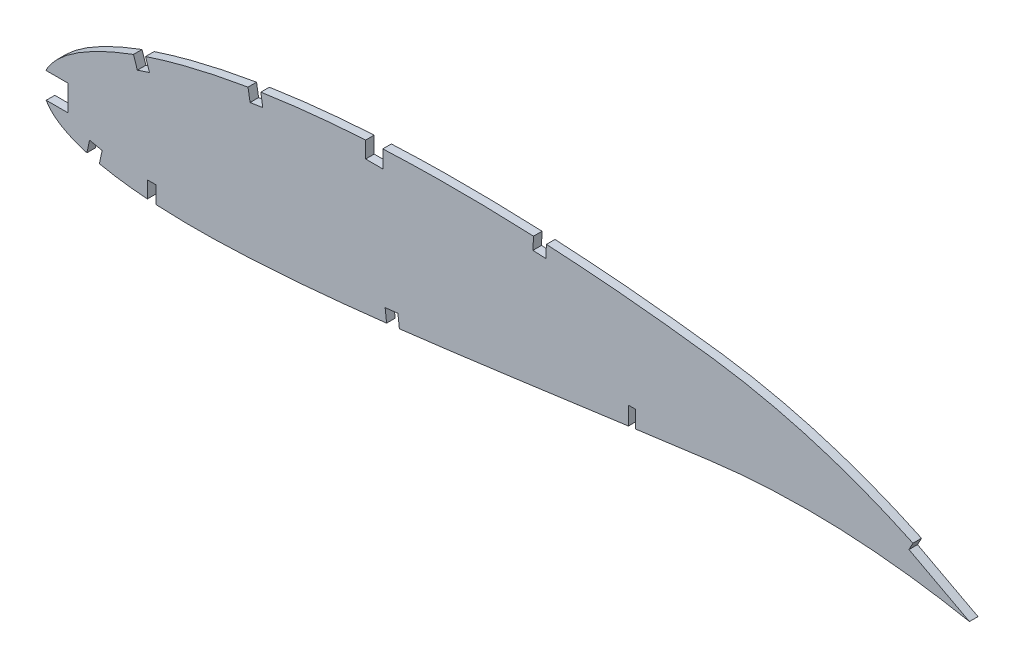
SolidWorks part; units mm, degrees
ref_plane "Front Plane" through (0, 0, 0) normal (0, 0, 1) x (1, 0, 0)
ref_plane "Top Plane" through (0, 0, 0) normal (0, 1, 0) x (1, 0, 0)
ref_plane "Right Plane" through (0, 0, 0) normal (1, 0, 0) x (0, 0, -1)
curve "Curve4"
  spline degree 3 poles (349.8746, 0.5455, 0) (349.8478, 0.562, 0) (349.7407, 0.6282, 0) (349.4993, 0.7762, 0) (349.0975, 1.0228, 0) (348.5349, 1.3661, 0) (347.8121, 1.8054, 0) (346.9286, 2.3375, 0) (345.885, 2.9606, 0) (344.6816, 3.6719, 0) (343.3185, 4.4681, 0) (341.7962, 5.3458, 0) (340.1148, 6.3001, 0) (338.275, 7.3272, 0) (336.2775, 8.422, 0) (334.1225, 9.5798, 0) (331.8109, 10.7946, 0) (329.3436, 12.0612, 0) (326.721, 13.3725, 0) (323.9443, 14.7232, 0) (321.0145, 16.1064, 0) (317.9326, 17.5149, 0) (314.7004, 18.9428, 0) (311.3186, 20.3813, 0) (307.7893, 21.8242, 0) (304.114, 23.2633, 0) (300.2949, 24.6919, 0) (296.3333, 26.1008, 0) (292.2323, 27.484, 0) (287.9939, 28.8323, 0) (283.6211, 30.1385, 0) (279.1164, 31.3942, 0) (274.4837, 32.5927, 0) (269.7257, 33.7256, 0) (264.8466, 34.785, 0) (259.8503, 35.7648, 0) (254.7409, 36.655, 0) (249.5326, 37.455, 0) (244.3091, 38.1205, 0) (239.0964, 38.7732, 0) (233.8915, 39.3864, 0) (228.623, 39.9736, 0) (223.2959, 40.5315, 0) (217.9156, 41.0583, 0) (212.4874, 41.5519, 0) (207.0171, 42.0107, 0) (201.5099, 42.4322, 0) (195.9716, 42.8157, 0) (190.4077, 43.1578, 0) (184.8241, 43.4583, 0) (179.2266, 43.7151, 0) (173.6208, 43.9264, 0) (168.0128, 44.0909, 0) (162.4085, 44.2071, 0) (156.8137, 44.2742, 0) (151.2345, 44.2904, 0) (145.6768, 44.2555, 0) (140.1465, 44.1681, 0) (134.6496, 44.0271, 0) (129.192, 43.8323, 0) (123.7796, 43.5837, 0) (118.4182, 43.2792, 0) (113.1138, 42.9209, 0) (107.8721, 42.5071, 0) (102.6991, 42.0378, 0) (97.6, 41.5149, 0) (92.5806, 40.937, 0) (87.6463, 40.3058, 0) (82.8024, 39.6225, 0) (78.0545, 38.8867, 0) (73.4074, 38.1005, 0) (68.8664, 37.2648, 0) (64.4362, 36.3819, 0) (60.1215, 35.4522, 0) (55.9271, 34.4784, 0) (51.8572, 33.4622, 0) (47.9162, 32.4055, 0) (44.1081, 31.3108, 0) (40.4368, 30.1806, 0) (36.9066, 29.0161, 0) (33.52, 27.8218, 0) (30.2813, 26.5985, 0) (27.193, 25.3499, 0) (24.2586, 24.0778, 0) (21.4804, 22.7861, 0) (18.8615, 21.4761, 0) (16.4038, 20.1517, 0) (14.1097, 18.8148, 0) (11.9815, 17.4679, 0) (10.02, 16.1143, 0) (8.2279, 14.7551, 0) (6.606, 13.3936, 0) (5.1551, 12.0318, 0) (3.8773, 10.6708, 0) (2.7727, 9.3129, 0) (1.8427, 7.9591, 0) (1.0874, 6.6108, 0) (0.5085, 5.269, 0) (0.1055, 3.9344, 0) (-0.1151, 2.6089, 0) (-0.17, 1.2916, 0) (-0.0566, 0.4299, 0) (0, 0, 0) knots 0 0 0 0 0.000254 0.001015 0.002283 0.004057 0.006331 0.009105 0.012374 0.016134 0.02038 0.025106 0.030306 0.035972 0.0421 0.048678 0.055702 0.06316 0.071046 0.07935 0.088063 0.097176 0.106678 0.116562 0.126814 0.137428 0.148394 0.1597 0.171338 0.183298 0.19557 0.208144 0.221012 0.234162 0.247587 0.261277 0.275223 0.289414 0.303771 0.317689 0.331784 0.34604 0.360444 0.374983 0.38964 0.404403 0.419257 0.434187 0.449177 0.464215 0.479284 0.49437 0.509458 0.524532 0.539579 0.554583 0.56953 0.584403 0.599191 0.613877 0.628447 0.642889 0.657186 0.671326 0.685294 0.699078 0.712665 0.726043 0.739198 0.752118 0.764792 0.777208 0.789356 0.801224 0.812804 0.824083 0.835055 0.84571 0.856038 0.866034 0.875689 0.884998 0.893953 0.902553 0.910789 0.918661 0.926166 0.933303 0.940071 0.946475 0.952518 0.958205 0.963547 0.968557 0.97325 0.977651 0.981787 0.985694 0.989415 0.993001 0.996508 1 1 1 1
curve "Curve5"
  spline degree 3 poles (0, 0, 0) (0.0898, -0.4241, 0) (0.27, -1.2744, 0) (0.7593, -2.4983, 0) (1.4064, -3.6749, 0) (2.2249, -4.801, 0) (3.2093, -5.8763, 0) (4.3574, -6.9018, 0) (5.6682, -7.8772, 0) (7.1398, -8.8018, 0) (8.7703, -9.6767, 0) (10.5577, -10.5014, 0) (12.5004, -11.2756, 0) (14.5962, -11.9982, 0) (16.8428, -12.6703, 0) (19.2378, -13.2904, 0) (21.7785, -13.8593, 0) (24.4626, -14.3755, 0) (27.2871, -14.8396, 0) (30.2491, -15.2513, 0) (33.3455, -15.6108, 0) (36.5732, -15.9174, 0) (39.9292, -16.1718, 0) (43.41, -16.3741, 0) (47.0123, -16.5249, 0) (50.7326, -16.6238, 0) (54.5673, -16.6722, 0) (58.5129, -16.6709, 0) (62.5656, -16.6195, 0) (66.7219, -16.5208, 0) (70.9777, -16.3742, 0) (75.3293, -16.1816, 0) (79.7728, -15.9448, 0) (84.3041, -15.6646, 0) (88.9192, -15.3423, 0) (93.6142, -14.9805, 0) (98.3848, -14.58, 0) (103.2269, -14.1432, 0) (108.136, -13.6724, 0) (113.1081, -13.1689, 0) (118.1387, -12.6351, 0) (123.2233, -12.0729, 0) (128.3576, -11.4851, 0) (133.537, -10.8728, 0) (138.7569, -10.2396, 0) (144.0126, -9.5866, 0) (149.2997, -8.9164, 0) (154.6133, -8.2321, 0) (159.9485, -7.5337, 0) (165.3008, -6.826, 0) (170.6651, -6.1086, 0) (176.0366, -5.3852, 0) (181.4105, -4.6578, 0) (186.7814, -3.9269, 0) (192.1447, -3.1954, 0) (197.4954, -2.4653, 0) (202.8282, -1.7368, 0) (208.1384, -1.0133, 0) (213.4205, -0.2949, 0) (218.6696, 0.417, 0) (223.8809, 1.1204, 0) (229.0493, 1.8142, 0) (234.1695, 2.4981, 0) (239.2364, 3.1723, 0) (244.169, 3.8163, 0) (248.9545, 4.4645, 0) (253.6088, 4.9959, 0) (258.2053, 5.4495, 0) (262.7485, 5.8213, 0) (267.2331, 6.1168, 0) (271.654, 6.3381, 0) (276.0058, 6.4882, 0) (280.283, 6.5716, 0) (284.4804, 6.5904, 0) (288.5922, 6.5507, 0) (292.613, 6.4555, 0) (296.5372, 6.3093, 0) (300.3594, 6.1169, 0) (304.0742, 5.8836, 0) (307.6759, 5.6128, 0) (311.1595, 5.3108, 0) (314.5196, 4.9821, 0) (317.7512, 4.6304, 0) (320.8494, 4.263, 0) (323.8094, 3.8825, 0) (326.6267, 3.4951, 0) (329.2966, 3.1046, 0) (331.8151, 2.7161, 0) (334.1781, 2.3332, 0) (336.3819, 1.9612, 0) (338.423, 1.6033, 0) (340.2977, 1.2632, 0) (342.0037, 0.9451, 0) (343.5374, 0.6506, 0) (344.8968, 0.3845, 0) (346.0794, 0.1481, 0) (347.0834, -0.0554, 0) (347.9072, -0.2251, 0) (348.5494, -0.3583, 0) (349.0088, -0.4551, 0) (349.2849, -0.5128, 0) (349.4076, -0.5389, 0) (349.4382, -0.5455, 0) knots 0 0 0 0 0.003638 0.007293 0.011028 0.014901 0.018963 0.023258 0.027821 0.032679 0.037853 0.043362 0.049215 0.055422 0.061989 0.068918 0.076211 0.083868 0.091887 0.100266 0.109 0.118085 0.127515 0.137285 0.147388 0.157816 0.168563 0.179619 0.190977 0.202627 0.21456 0.226767 0.239236 0.251959 0.264924 0.27812 0.291536 0.30516 0.318981 0.332985 0.347163 0.361499 0.375981 0.390597 0.405333 0.420175 0.43511 0.450124 0.465203 0.480333 0.495501 0.51069 0.525887 0.541078 0.556247 0.571382 0.586466 0.601485 0.616424 0.631269 0.646007 0.660621 0.675098 0.689423 0.703582 0.716908 0.730009 0.742952 0.755726 0.76832 0.780724 0.792927 0.804916 0.816679 0.828204 0.839475 0.850481 0.861208 0.871639 0.881763 0.891564 0.901027 0.910139 0.918884 0.927249 0.935221 0.942785 0.949928 0.956638 0.962904 0.968712 0.974054 0.978918 0.983297 0.98718 0.990561 0.993433 0.995791 0.99763 0.998946 0.999737 1 1 1 1
sketch "Sketch1" plane through (0, 0, 0) normal (0, 0, 1) x (1, 0, 0)
  line L24 (349.8746, 0.5455) -> (352.7074, -1.2046)
  line L25 (349.4382, -0.5455) -> (352.7074, -1.2046)
  spline S1 degree 3 poles (-4826.1735, -1302.2326) (84.7421, 69.7383) (-8.0065, 19.4278) (0.7593, -2.4983) (1.4064, -3.6749) (2.2249, -4.801) (3.2093, -5.8763) (4.3574, -6.9018) (5.6682, -7.8772) (7.1398, -8.8018) (8.7703, -9.6767) (10.5577, -10.5014) (12.5004, -11.2756) (14.5962, -11.9982) (16.8428, -12.6703) (19.2378, -13.2904) (21.7785, -13.8593) (24.4626, -14.3755) (27.2871, -14.8396) (30.2491, -15.2513) (33.3455, -15.6108) (36.5732, -15.9174) (39.9292, -16.1718) (43.41, -16.3741) (47.0123, -16.5249) (50.7326, -16.6238) (54.5673, -16.6722) (58.5129, -16.6709) (62.5656, -16.6195) (66.7219, -16.5208) (70.9777, -16.3742) (75.3293, -16.1816) (79.7728, -15.9448) (84.3041, -15.6646) (88.9192, -15.3423) (93.6142, -14.9805) (98.3848, -14.58) (103.2269, -14.1432) (108.136, -13.6724) (113.1081, -13.1689) (118.1387, -12.6351) (123.2233, -12.0729) (128.3576, -11.4851) (133.537, -10.8728) (138.7569, -10.2396) (144.0126, -9.5866) (149.2997, -8.9164) (154.6133, -8.2321) (159.9485, -7.5337) (165.3008, -6.826) (170.6651, -6.1086) (176.0366, -5.3852) (181.4105, -4.6578) (186.7814, -3.9269) (192.1447, -3.1954) (197.4954, -2.4653) (202.8282, -1.7368) (208.1384, -1.0133) (213.4205, -0.2949) (218.6696, 0.417) (223.8809, 1.1204) (229.0493, 1.8142) (234.1695, 2.4981) (239.2364, 3.1723) (244.169, 3.8163) (248.9545, 4.4645) (253.6088, 4.9959) (258.2053, 5.4495) (262.7485, 5.8213) (267.2331, 6.1168) (271.654, 6.3381) (276.0058, 6.4882) (280.283, 6.5716) (284.4804, 6.5904) (288.5922, 6.5507) (292.613, 6.4555) (296.5372, 6.3093) (300.3594, 6.1169) (304.0742, 5.8836) (307.6759, 5.6128) (311.1595, 5.3108) (314.5196, 4.9821) (317.7512, 4.6304) (320.8494, 4.263) (323.8094, 3.8825) (326.6267, 3.4951) (329.2966, 3.1046) (331.8151, 2.7161) (334.1781, 2.3332) (336.3819, 1.9612) (338.423, 1.6033) (340.2977, 1.2632) (342.0037, 0.9451) (343.5374, 0.6506) (344.8968, 0.3845) (346.0794, 0.1481) (347.0834, -0.0554) (347.9072, -0.2251) (348.5494, -0.3583) (349.0088, -0.4551) (365.4113, -3.8787) (379.663, -16.7158) (1432.0031, 4879.4073) knots -0.18653 -0.18653 -0.18653 -0.18653 0.003638 0.007293 0.011028 0.014901 0.018963 0.023258 0.027821 0.032679 0.037853 0.043362 0.049215 0.055422 0.061989 0.068918 0.076211 0.083868 0.091887 0.100266 0.109 0.118085 0.127515 0.137285 0.147388 0.157816 0.168563 0.179619 0.190977 0.202627 0.21456 0.226767 0.239236 0.251959 0.264924 0.27812 0.291536 0.30516 0.318981 0.332985 0.347163 0.361499 0.375981 0.390597 0.405333 0.420175 0.43511 0.450124 0.465203 0.480333 0.495501 0.51069 0.525887 0.541078 0.556247 0.571382 0.586466 0.601485 0.616424 0.631269 0.646007 0.660621 0.675098 0.689423 0.703582 0.716908 0.730009 0.742952 0.755726 0.76832 0.780724 0.792927 0.804916 0.816679 0.828204 0.839475 0.850481 0.861208 0.871639 0.881763 0.891564 0.901027 0.910139 0.918884 0.927249 0.935221 0.942785 0.949928 0.956638 0.962904 0.968712 0.974054 0.978918 0.983297 0.98718 0.990561 0.993433 0.995791 0.99763 0.998946 0.999737 1.138459 1.138459 1.138459 1.138459 only from (0, 0) to (349.4382, -0.5455) construction
  spline S3 degree 3 poles (3018.3823, 4226.7606) (376.7158, -26.0809) (365.4465, -9.0056) (349.4993, 0.7762) (349.0975, 1.0228) (348.5349, 1.3661) (347.8121, 1.8054) (346.9286, 2.3375) (345.885, 2.9606) (344.6816, 3.6719) (343.3185, 4.4681) (341.7962, 5.3458) (340.1148, 6.3001) (338.275, 7.3272) (336.2775, 8.422) (334.1225, 9.5798) (331.8109, 10.7946) (329.3436, 12.0612) (326.721, 13.3725) (323.9443, 14.7232) (321.0145, 16.1064) (317.9326, 17.5149) (314.7004, 18.9428) (311.3186, 20.3813) (307.7893, 21.8242) (304.114, 23.2633) (300.2949, 24.6919) (296.3333, 26.1008) (292.2323, 27.484) (287.9939, 28.8323) (283.6211, 30.1385) (279.1164, 31.3942) (274.4837, 32.5927) (269.7257, 33.7256) (264.8466, 34.785) (259.8503, 35.7648) (254.7409, 36.655) (249.5326, 37.455) (244.3091, 38.1205) (239.0964, 38.7732) (233.8915, 39.3864) (228.623, 39.9736) (223.2959, 40.5315) (217.9156, 41.0583) (212.4874, 41.5519) (207.0171, 42.0107) (201.5099, 42.4322) (195.9716, 42.8157) (190.4077, 43.1578) (184.8241, 43.4583) (179.2266, 43.7151) (173.6208, 43.9264) (168.0128, 44.0909) (162.4085, 44.2071) (156.8137, 44.2742) (151.2345, 44.2904) (145.6768, 44.2555) (140.1465, 44.1681) (134.6496, 44.0271) (129.192, 43.8323) (123.7796, 43.5837) (118.4182, 43.2792) (113.1138, 42.9209) (107.8721, 42.5071) (102.6991, 42.0378) (97.6, 41.5149) (92.5806, 40.937) (87.6463, 40.3058) (82.8024, 39.6225) (78.0545, 38.8867) (73.4074, 38.1005) (68.8664, 37.2648) (64.4362, 36.3819) (60.1215, 35.4522) (55.9271, 34.4784) (51.8572, 33.4622) (47.9162, 32.4055) (44.1081, 31.3108) (40.4368, 30.1806) (36.9066, 29.0161) (33.52, 27.8218) (30.2813, 26.5985) (27.193, 25.3499) (24.2586, 24.0778) (21.4804, 22.7861) (18.8615, 21.4761) (16.4038, 20.1517) (14.1097, 18.8148) (11.9815, 17.4679) (10.02, 16.1143) (8.2279, 14.7551) (6.606, 13.3936) (5.1551, 12.0318) (3.8773, 10.6708) (2.7727, 9.3129) (1.8427, 7.9591) (1.0874, 6.6108) (0.5085, 5.269) (0.1055, 3.9344) (-0.1151, 2.6089) (-1.0968, -20.9427) (103.3134, -37.4738) (-4984.07, -377.4853) knots -0.148602 -0.148602 -0.148602 -0.148602 0.000254 0.001015 0.002283 0.004057 0.006331 0.009105 0.012374 0.016134 0.02038 0.025106 0.030306 0.035972 0.0421 0.048678 0.055702 0.06316 0.071046 0.07935 0.088063 0.097176 0.106678 0.116562 0.126814 0.137428 0.148394 0.1597 0.171338 0.183298 0.19557 0.208144 0.221012 0.234162 0.247587 0.261277 0.275223 0.289414 0.303771 0.317689 0.331784 0.34604 0.360444 0.374983 0.38964 0.404403 0.419257 0.434187 0.449177 0.464215 0.479284 0.49437 0.509458 0.524532 0.539579 0.554583 0.56953 0.584403 0.599191 0.613877 0.628447 0.642889 0.657186 0.671326 0.685294 0.699078 0.712665 0.726043 0.739198 0.752118 0.764792 0.777208 0.789356 0.801224 0.812804 0.824083 0.835055 0.84571 0.856038 0.866034 0.875689 0.884998 0.893953 0.902553 0.910789 0.918661 0.926166 0.933303 0.940071 0.946475 0.952518 0.958205 0.963547 0.968557 0.97325 0.977651 0.981787 0.985694 0.989415 0.993001 0.996508 1.178653 1.178653 1.178653 1.178653 only from (349.8746, 0.5455) to (0, 0) construction
  spline S4 degree 3 poles (0, 0) (0.0898, -0.4241) (0.27, -1.2744) (0.7593, -2.4983) (1.4064, -3.6749) (2.2249, -4.801) (3.2093, -5.8763) (4.3574, -6.9018) (5.6682, -7.8772) (7.1398, -8.8018) (8.7703, -9.6767) (10.5577, -10.5014) (12.5004, -11.2756) (14.5962, -11.9982) (16.8428, -12.6703) (19.2378, -13.2904) (21.7785, -13.8593) (24.4626, -14.3755) (27.2871, -14.8396) (30.2491, -15.2513) (33.3455, -15.6108) (36.5732, -15.9174) (39.9292, -16.1718) (43.41, -16.3741) (47.0123, -16.5249) (50.7326, -16.6238) (54.5673, -16.6722) (58.5129, -16.6709) (62.5656, -16.6195) (66.7219, -16.5208) (70.9777, -16.3742) (75.3293, -16.1816) (79.7728, -15.9448) (84.3041, -15.6646) (88.9192, -15.3423) (93.6142, -14.9805) (98.3848, -14.58) (103.2269, -14.1432) (108.136, -13.6724) (113.1081, -13.1689) (118.1387, -12.6351) (123.2233, -12.0729) (128.3576, -11.4851) (133.537, -10.8728) (138.7569, -10.2396) (144.0126, -9.5866) (149.2997, -8.9164) (154.6133, -8.2321) (159.9485, -7.5337) (165.3008, -6.826) (170.6651, -6.1086) (176.0366, -5.3852) (181.4105, -4.6578) (186.7814, -3.9269) (192.1447, -3.1954) (197.4954, -2.4653) (202.8282, -1.7368) (208.1384, -1.0133) (213.4205, -0.2949) (218.6696, 0.417) (223.8809, 1.1204) (229.0493, 1.8142) (234.1695, 2.4981) (239.2364, 3.1723) (244.169, 3.8163) (248.9545, 4.4645) (253.6088, 4.9959) (258.2053, 5.4495) (262.7485, 5.8213) (267.2331, 6.1168) (271.654, 6.3381) (276.0058, 6.4882) (280.283, 6.5716) (284.4804, 6.5904) (288.5922, 6.5507) (292.613, 6.4555) (296.5372, 6.3093) (300.3594, 6.1169) (304.0742, 5.8836) (307.6759, 5.6128) (311.1595, 5.3108) (314.5196, 4.9821) (317.7512, 4.6304) (320.8494, 4.263) (323.8094, 3.8825) (326.6267, 3.4951) (329.2966, 3.1046) (331.8151, 2.7161) (334.1781, 2.3332) (336.3819, 1.9612) (338.423, 1.6033) (340.2977, 1.2632) (342.0037, 0.9451) (343.5374, 0.6506) (344.8968, 0.3845) (346.0794, 0.1481) (347.0834, -0.0554) (347.9072, -0.2251) (348.5494, -0.3583) (349.0088, -0.4551) (349.2849, -0.5128) (349.4076, -0.5389) (349.4382, -0.5455) knots 0 0 0 0 0.003638 0.007293 0.011028 0.014901 0.018963 0.023258 0.027821 0.032679 0.037853 0.043362 0.049215 0.055422 0.061989 0.068918 0.076211 0.083868 0.091887 0.100266 0.109 0.118085 0.127515 0.137285 0.147388 0.157816 0.168563 0.179619 0.190977 0.202627 0.21456 0.226767 0.239236 0.251959 0.264924 0.27812 0.291536 0.30516 0.318981 0.332985 0.347163 0.361499 0.375981 0.390597 0.405333 0.420175 0.43511 0.450124 0.465203 0.480333 0.495501 0.51069 0.525887 0.541078 0.556247 0.571382 0.586466 0.601485 0.616424 0.631269 0.646007 0.660621 0.675098 0.689423 0.703582 0.716908 0.730009 0.742952 0.755726 0.76832 0.780724 0.792927 0.804916 0.816679 0.828204 0.839475 0.850481 0.861208 0.871639 0.881763 0.891564 0.901027 0.910139 0.918884 0.927249 0.935221 0.942785 0.949928 0.956638 0.962904 0.968712 0.974054 0.978918 0.983297 0.98718 0.990561 0.993433 0.995791 0.99763 0.998946 0.999737 1 1 1 1
  spline S5 degree 3 poles (349.8746, 0.5455) (349.8478, 0.562) (349.7407, 0.6282) (349.4993, 0.7762) (349.0975, 1.0228) (348.5349, 1.3661) (347.8121, 1.8054) (346.9286, 2.3375) (345.885, 2.9606) (344.6816, 3.6719) (343.3185, 4.4681) (341.7962, 5.3458) (340.1148, 6.3001) (338.275, 7.3272) (336.2775, 8.422) (334.1225, 9.5798) (331.8109, 10.7946) (329.3436, 12.0612) (326.721, 13.3725) (323.9443, 14.7232) (321.0145, 16.1064) (317.9326, 17.5149) (314.7004, 18.9428) (311.3186, 20.3813) (307.7893, 21.8242) (304.114, 23.2633) (300.2949, 24.6919) (296.3333, 26.1008) (292.2323, 27.484) (287.9939, 28.8323) (283.6211, 30.1385) (279.1164, 31.3942) (274.4837, 32.5927) (269.7257, 33.7256) (264.8466, 34.785) (259.8503, 35.7648) (254.7409, 36.655) (249.5326, 37.455) (244.3091, 38.1205) (239.0964, 38.7732) (233.8915, 39.3864) (228.623, 39.9736) (223.2959, 40.5315) (217.9156, 41.0583) (212.4874, 41.5519) (207.0171, 42.0107) (201.5099, 42.4322) (195.9716, 42.8157) (190.4077, 43.1578) (184.8241, 43.4583) (179.2266, 43.7151) (173.6208, 43.9264) (168.0128, 44.0909) (162.4085, 44.2071) (156.8137, 44.2742) (151.2345, 44.2904) (145.6768, 44.2555) (140.1465, 44.1681) (134.6496, 44.0271) (129.192, 43.8323) (123.7796, 43.5837) (118.4182, 43.2792) (113.1138, 42.9209) (107.8721, 42.5071) (102.6991, 42.0378) (97.6, 41.5149) (92.5806, 40.937) (87.6463, 40.3058) (82.8024, 39.6225) (78.0545, 38.8867) (73.4074, 38.1005) (68.8664, 37.2648) (64.4362, 36.3819) (60.1215, 35.4522) (55.9271, 34.4784) (51.8572, 33.4622) (47.9162, 32.4055) (44.1081, 31.3108) (40.4368, 30.1806) (36.9066, 29.0161) (33.52, 27.8218) (30.2813, 26.5985) (27.193, 25.3499) (24.2586, 24.0778) (21.4804, 22.7861) (18.8615, 21.4761) (16.4038, 20.1517) (14.1097, 18.8148) (11.9815, 17.4679) (10.02, 16.1143) (8.2279, 14.7551) (6.606, 13.3936) (5.1551, 12.0318) (3.8773, 10.6708) (2.7727, 9.3129) (1.8427, 7.9591) (1.0874, 6.6108) (0.5085, 5.269) (0.1055, 3.9344) (-0.1151, 2.6089) (-0.17, 1.2916) (-0.0566, 0.4299) (0, 0) knots 0 0 0 0 0.000254 0.001015 0.002283 0.004057 0.006331 0.009105 0.012374 0.016134 0.02038 0.025106 0.030306 0.035972 0.0421 0.048678 0.055702 0.06316 0.071046 0.07935 0.088063 0.097176 0.106678 0.116562 0.126814 0.137428 0.148394 0.1597 0.171338 0.183298 0.19557 0.208144 0.221012 0.234162 0.247587 0.261277 0.275223 0.289414 0.303771 0.317689 0.331784 0.34604 0.360444 0.374983 0.38964 0.404403 0.419257 0.434187 0.449177 0.464215 0.479284 0.49437 0.509458 0.524532 0.539579 0.554583 0.56953 0.584403 0.599191 0.613877 0.628447 0.642889 0.657186 0.671326 0.685294 0.699078 0.712665 0.726043 0.739198 0.752118 0.764792 0.777208 0.789356 0.801224 0.812804 0.824083 0.835055 0.84571 0.856038 0.866034 0.875689 0.884998 0.893953 0.902553 0.910789 0.918661 0.926166 0.933303 0.940071 0.946475 0.952518 0.958205 0.963547 0.968557 0.97325 0.977651 0.981787 0.985694 0.989415 0.993001 0.996508 1 1 1 1
extrude "Boss-Extrude1" add sketch "Sketch1" along normal blind 3.175
sketch "Sketch2" plane through (0, 0, 0) normal (0, 0, -1) x (-1, 0, 0)
  line L0 (-219.6066, 6.9148) -> (-217.0666, 6.9148)
  line L1 (-219.6066, 0.5647) -> (-219.6066, 6.9148)
  line L2 (-217.0666, 0.5647) -> (-217.0666, -0.7899)
  line L3 (-125.9441, 43.5934) -> (-125.9441, 37.241)
  line L4 (-217.0666, -0.7899) -> (-219.6066, -0.1126)
  line L5 (-41.8066, -16.2784) -> (-41.8066, -9.9284)
  line L6 (-219.6066, -0.1126) -> (-219.6066, 0.5647)
  line L7 (-38.6316, -16.2784) -> (-38.6316, -9.9284)
  line L8 (-125.9441, 37.241) -> (-119.5941, 37.241)
  line L9 (-119.5941, 43.5934) -> (-119.5941, 37.241)
  line L10 (-125.9441, 43.5934) -> (-125.9441, 46.4957)
  line L11 (-217.0666, 0.5647) -> (-217.0666, 6.9148)
  line L12 (-125.9441, 46.4957) -> (-119.5941, 44.8024)
  line L13 (-119.5941, 44.8024) -> (-119.5941, 43.5934)
  line L14 (-41.8066, -16.2784) -> (-38.6316, -16.2784)
  line L15 (-41.8066, -9.9284) -> (-38.6316, -9.9284)
extrude "Cut-Extrude1" cut sketch "Sketch2" against normal blind 7.62
sketch "Sketch3" plane through (0, 0, 3.175) normal (0, 0, 1) x (1, 0, 0)
  line L1 (-0.4071, 6.4083) -> (9.1179, 6.4083)
  line L2 (16.1715, -12.5452) -> (15.7059, -14.4019)
  line L3 (9.1179, -3.1167) -> (9.1179, 6.4083)
  line L4 (20.793, -13.704) -> (20.3275, -15.5607)
  line L5 (39.4213, 24.9477) -> (37.9149, 29.4655)
  line L6 (15.7059, -14.4019) -> (20.3275, -15.5607)
  line L7 (20.793, -13.704) -> (21.8392, -8.9067)
  line L9 (21.8392, -8.9067) -> (17.1861, -7.8921)
  line L10 (127.3683, -11.6175) -> (127.6344, -13.8855)
  line L11 (81.4236, 34.6803) -> (80.6994, 39.3875)
  line L12 (132.1136, -11.0609) -> (132.3796, -13.3289)
  line L13 (132.1136, -11.0609) -> (131.5505, -6.3243)
  line L14 (127.6344, -13.8855) -> (132.3796, -13.3289)
  line L15 (131.5505, -6.3243) -> (126.8213, -6.8865)
  line L17 (186.4034, 38.6915) -> (186.6522, 43.4474)
  line L19 (-0.4071, -3.1167) -> (-0.4071, 6.4083)
  line L21 (-0.4071, -3.1167) -> (9.1179, -3.1167)
  line L23 (33.4172, 27.8983) -> (34.9034, 23.4412)
  line L25 (34.9034, 23.4412) -> (39.4213, 24.9477)
  line L27 (17.1861, -7.8921) -> (16.1715, -12.5452)
  line L29 (75.932, 38.6201) -> (76.7164, 33.9561)
  line L31 (76.7164, 33.9561) -> (81.4236, 34.6803)
  line L33 (126.8213, -6.8865) -> (127.3683, -11.6175)
  line L35 (181.8631, 43.6817) -> (181.6474, 38.9402)
  line L37 (181.6474, 38.9402) -> (186.4034, 38.6915)
  arc A1 (186.6522, 43.4474) -> (181.8631, 43.6817) centre (149.7221, -662.3427) ccw
  spline S1 degree 3 poles (37.9149, 29.4655) (37.5031, 29.3282) (35.9987, 28.8207) (34.5011, 28.2932) (33.4172, 27.8983) knots 0 0 0 0 0.273428 1 1 1 1
  spline S3 degree 3 poles (80.6994, 39.3875) (79.7758, 39.2454) (78.1859, 38.9943) (76.5977, 38.7321) (75.932, 38.6201) knots 0 0 0 0 0.580571 1 1 1 1
extrude "Cut-Extrude2" cut sketch "Sketch3" against normal blind 7.62
sketch "Sketch4" plane through (0, 0, 3.175) normal (0, 0, 1) x (1, 0, 0)
  line L0 (322.6191, 15.347) -> (321.1318, 12.542)
  line L1 (322.6191, 15.347) -> (345.0596, 3.448)
  line L2 (321.1318, 12.542) -> (343.5722, 0.6429)
  line L3 (345.0596, 3.448) -> (343.5722, 0.6429)
  line L29 (1.0177, 6.4083) -> (9.1179, 6.4083)
  line L30 (9.1179, 6.4083) -> (9.1179, -3.1167)
  line L31 (9.1179, -3.1167) -> (1.1073, -3.1167)
  line L32 (16.1882, -12.4685) -> (17.1861, -7.8921)
  line L33 (17.1861, -7.8921) -> (21.8392, -8.9067)
  line L34 (21.8392, -8.9067) -> (20.8074, -13.6378)
  line L35 (38.6316, -16.0704) -> (38.6316, -9.9284)
  line L36 (38.6316, -9.9284) -> (41.8066, -9.9284)
  line L37 (41.8066, -9.9284) -> (41.8066, -16.2784)
  line L38 (127.366, -11.5969) -> (126.8213, -6.8865)
  line L39 (126.8213, -6.8865) -> (131.5505, -6.3243)
  line L40 (131.5505, -6.3243) -> (132.1111, -11.0403)
  line L41 (217.0666, 0.1994) -> (217.0666, 6.9148)
  line L42 (217.0666, 6.9148) -> (219.6066, 6.9148)
  line L43 (219.6066, 6.9148) -> (219.6066, 0.5432)
  line L44 (349.4382, -0.5455) -> (352.7074, -1.2046)
  line L45 (352.7074, -1.2046) -> (349.8746, 0.5455)
  line L46 (186.6475, 43.3577) -> (186.4034, 38.6915)
  line L47 (186.4034, 38.6915) -> (181.6474, 38.9402)
  line L48 (181.6474, 38.9402) -> (181.8591, 43.5924)
  line L49 (125.9441, 43.6804) -> (125.9441, 37.241)
  line L50 (125.9441, 37.241) -> (119.5941, 37.241)
  line L51 (119.5941, 37.241) -> (119.5941, 43.3413)
  line L52 (80.7135, 39.2958) -> (81.4236, 34.6803)
  line L53 (81.4236, 34.6803) -> (76.7164, 33.9561)
  line L54 (76.7164, 33.9561) -> (75.9476, 38.5273)
  line L55 (37.9515, 29.3559) -> (39.4213, 24.9477)
  line L56 (39.4213, 24.9477) -> (34.9034, 23.4412)
  line L57 (34.9034, 23.4412) -> (33.4552, 27.7843)
  line L58 (1.0177, 6.4083) -> (9.1179, 6.4083)
  line L59 (9.1179, 6.4083) -> (9.1179, -3.1167)
  line L60 (9.1179, -3.1167) -> (1.1073, -3.1167)
  line L61 (16.1882, -12.4685) -> (17.1861, -7.8921)
  line L62 (17.1861, -7.8921) -> (21.8392, -8.9067)
  line L63 (21.8392, -8.9067) -> (20.8074, -13.6378)
  line L64 (38.6316, -16.0704) -> (38.6316, -9.9284)
  line L65 (38.6316, -9.9284) -> (41.8066, -9.9284)
  line L66 (41.8066, -9.9284) -> (41.8066, -16.2784)
  line L67 (127.366, -11.5969) -> (126.8213, -6.8865)
  line L68 (126.8213, -6.8865) -> (131.5505, -6.3243)
  line L69 (131.5505, -6.3243) -> (132.1111, -11.0403)
  line L70 (217.0666, 0.1994) -> (217.0666, 6.9148)
  line L71 (217.0666, 6.9148) -> (219.6066, 6.9148)
  line L72 (219.6066, 6.9148) -> (219.6066, 0.5432)
  line L73 (349.4382, -0.5455) -> (352.7074, -1.2046)
  line L74 (352.7074, -1.2046) -> (349.8746, 0.5455)
  line L75 (186.6475, 43.3577) -> (186.4034, 38.6915)
  line L76 (186.4034, 38.6915) -> (181.6474, 38.9402)
  line L77 (181.6474, 38.9402) -> (181.8591, 43.5924)
  line L78 (125.9441, 43.6804) -> (125.9441, 37.241)
  line L79 (125.9441, 37.241) -> (119.5941, 37.241)
  line L80 (119.5941, 37.241) -> (119.5941, 43.3413)
  line L81 (80.7135, 39.2958) -> (81.4236, 34.6803)
  line L82 (81.4236, 34.6803) -> (76.7164, 33.9561)
  line L83 (76.7164, 33.9561) -> (75.9476, 38.5273)
  line L84 (37.9515, 29.3559) -> (39.4213, 24.9477)
  line L85 (39.4213, 24.9477) -> (34.9034, 23.4412)
  line L86 (34.9034, 23.4412) -> (33.4552, 27.7843)
  spline S10 degree 3 poles (-2134.0221, 3364.7605) (538.8254, -195.9198) (211.3259, 99.792) (27.193, 25.3499) (24.2586, 24.0778) (21.4804, 22.7861) (18.8615, 21.4761) (16.4038, 20.1517) (14.1097, 18.8148) (11.9815, 17.4679) (10.02, 16.1143) (8.2279, 14.7551) (6.606, 13.3936) (5.1551, 12.0318) (3.8773, 10.6708) (2.7727, 9.3129) (1.8427, 7.9591) (-20.1055, -31.2195) (140.4638, -160.6153) (3982.6931, 317.4313) knots -0.699136 -0.699136 -0.699136 -0.699136 0.884998 0.893953 0.902553 0.910789 0.918661 0.926166 0.933303 0.940071 0.946475 0.952518 0.958205 0.963547 0.968557 0.97325 0.977651 0.981787 1.334861 1.334861 1.334861 1.334861 only from (33.4552, 27.7843) to (1.0177, 6.4083)
  spline S11 degree 3 poles (2938.0839, -2689.8405) (246.7778, 269.8068) (-28.0545, 36.8583) (2.2249, -4.801) (3.2093, -5.8763) (4.3574, -6.9018) (5.6682, -7.8772) (7.1398, -8.8018) (8.7703, -9.6767) (10.5577, -10.5014) (12.5004, -11.2756) (106.4904, -43.6815) (280.4844, 176.1899) (-1938.6252, -3496.6913) knots -0.412769 -0.412769 -0.412769 -0.412769 0.011028 0.014901 0.018963 0.023258 0.027821 0.032679 0.037853 0.043362 0.049215 0.055422 0.878689 0.878689 0.878689 0.878689 only from (1.1073, -3.1167) to (16.1882, -12.4685)
  spline S12 degree 3 poles (1320.3281, 3756.9994) (-146.0598, 213.5353) (-80.6979, 5.8491) (24.4626, -14.3755) (27.2871, -14.8396) (30.2491, -15.2513) (33.3455, -15.6108) (213.0584, -32.6822) (415.285, 227.9801) (-474.0394, -3957.3928) knots -0.808032 -0.808032 -0.808032 -0.808032 0.076211 0.083868 0.091887 0.100266 0.109 0.118085 1.617405 1.617405 1.617405 1.617405 only from (20.8074, -13.6378) to (38.6316, -16.0704)
  spline S13 degree 3 poles (256.2221, 3952.659) (-280.3063, 190.6076) (-122.0561, -9.444) (47.0123, -16.5249) (50.7326, -16.6238) (54.5673, -16.6722) (58.5129, -16.6709) (62.5656, -16.6195) (66.7219, -16.5208) (70.9777, -16.3742) (75.3293, -16.1816) (79.7728, -15.9448) (84.3041, -15.6646) (88.9192, -15.3423) (93.6142, -14.9805) (98.3848, -14.58) (103.2269, -14.1432) (108.136, -13.6724) (113.1081, -13.1689) (118.1387, -12.6351) (616.9364, 42.523) (1082.5995, 376.7415) (1720.9864, -3408.5986) knots -1.264346 -1.264346 -1.264346 -1.264346 0.137285 0.147388 0.157816 0.168563 0.179619 0.190977 0.202627 0.21456 0.226767 0.239236 0.251959 0.264924 0.27812 0.291536 0.30516 0.318981 0.332985 0.347163 0.361499 4.550792 4.550792 4.550792 4.550792 only from (41.8066, -16.2784) to (127.366, -11.5969)
  spline S14 degree 3 poles (-1205.6276, 3667.8196) (-512.3075, 1.844) (-182.27, -49.1822) (138.7569, -10.2396) (144.0126, -9.5866) (149.2997, -8.9164) (154.6133, -8.2321) (159.9485, -7.5337) (165.3008, -6.826) (170.6651, -6.1086) (176.0366, -5.3852) (181.4105, -4.6578) (186.7814, -3.9269) (192.1447, -3.1954) (197.4954, -2.4653) (202.8282, -1.7368) (208.1384, -1.0133) (637.4453, 57.377) (1067.6455, 95.9352) (1973.8247, -3421.787) knots -2.297748 -2.297748 -2.297748 -2.297748 0.390597 0.405333 0.420175 0.43511 0.450124 0.465203 0.480333 0.495501 0.51069 0.525887 0.541078 0.556247 0.571382 0.586466 0.601485 0.616424 4.2279 4.2279 4.2279 4.2279 only from (132.1111, -11.0403) to (217.0666, 0.1994)
  spline S15 degree 3 poles (-2257.0625, 2699.4045) (-1158.0495, -286.0267) (-472.0862, -92.3082) (229.0493, 1.8142) (234.1695, 2.4981) (239.2364, 3.1723) (244.169, 3.8163) (248.9545, 4.4645) (253.6088, 4.9959) (258.2053, 5.4495) (262.7485, 5.8213) (267.2331, 6.1168) (271.654, 6.3381) (276.0058, 6.4882) (280.283, 6.5716) (284.4804, 6.5904) (288.5922, 6.5507) (292.613, 6.4555) (296.5372, 6.3093) (300.3594, 6.1169) (304.0742, 5.8836) (307.6759, 5.6128) (311.1595, 5.3108) (314.5196, 4.9821) (317.7512, 4.6304) (320.8494, 4.263) (323.8094, 3.8825) (326.6267, 3.4951) (329.2966, 3.1046) (331.8151, 2.7161) (334.1781, 2.3332) (336.3819, 1.9612) (338.423, 1.6033) (340.2977, 1.2632) (342.0037, 0.9451) (343.5374, 0.6506) (344.8968, 0.3845) (346.0794, 0.1481) (347.0834, -0.0554) (347.9072, -0.2251) (348.5494, -0.3583) (349.0088, -0.4551) (364.249, -3.6361) (377.6138, -14.9276) (1220.6198, 3897.1166) knots -5.270622 -5.270622 -5.270622 -5.270622 0.646007 0.660621 0.675098 0.689423 0.703582 0.716908 0.730009 0.742952 0.755726 0.76832 0.780724 0.792927 0.804916 0.816679 0.828204 0.839475 0.850481 0.861208 0.871639 0.881763 0.891564 0.901027 0.910139 0.918884 0.927249 0.935221 0.942785 0.949928 0.956638 0.962904 0.968712 0.974054 0.978918 0.983297 0.98718 0.990561 0.993433 0.995791 0.99763 0.998946 0.999737 1.128479 1.128479 1.128479 1.128479 only from (219.6066, 0.5432) to (349.4382, -0.5455)
  spline S16 degree 3 poles (2490.5398, 3377.5083) (375.0876, -23.686) (364.3203, -8.3148) (349.4993, 0.7762) (349.0975, 1.0228) (348.5349, 1.3661) (347.8121, 1.8054) (346.9286, 2.3375) (345.885, 2.9606) (344.6816, 3.6719) (343.3185, 4.4681) (341.7962, 5.3458) (340.1148, 6.3001) (338.275, 7.3272) (336.2775, 8.422) (334.1225, 9.5798) (331.8109, 10.7946) (329.3436, 12.0612) (326.721, 13.3725) (323.9443, 14.7232) (321.0145, 16.1064) (317.9326, 17.5149) (314.7004, 18.9428) (311.3186, 20.3813) (307.7893, 21.8242) (304.114, 23.2633) (300.2949, 24.6919) (296.3333, 26.1008) (292.2323, 27.484) (287.9939, 28.8323) (283.6211, 30.1385) (279.1164, 31.3942) (274.4837, 32.5927) (269.7257, 33.7256) (264.8466, 34.785) (259.8503, 35.7648) (254.7409, 36.655) (249.5326, 37.455) (244.3091, 38.1205) (239.0964, 38.7732) (233.8915, 39.3864) (228.623, 39.9736) (223.2959, 40.5315) (217.9156, 41.0583) (212.4874, 41.5519) (207.0171, 42.0107) (201.5099, 42.4322) (195.9716, 42.8157) (-225.3258, 68.7211) (-665.6508, -267.5515) (-642.8416, -3720.9143) knots -0.137946 -0.137946 -0.137946 -0.137946 0.000254 0.001015 0.002283 0.004057 0.006331 0.009105 0.012374 0.016134 0.02038 0.025106 0.030306 0.035972 0.0421 0.048678 0.055702 0.06316 0.071046 0.07935 0.088063 0.097176 0.106678 0.116562 0.126814 0.137428 0.148394 0.1597 0.171338 0.183298 0.19557 0.208144 0.221012 0.234162 0.247587 0.261277 0.275223 0.289414 0.303771 0.317689 0.331784 0.34604 0.360444 0.374983 0.38964 0.404403 0.419257 0.434187 0.449177 3.823488 3.823488 3.823488 3.823488 only from (349.8746, 0.5455) to (186.6475, 43.3577)
  spline S17 degree 3 poles (397.9971, 3747.2003) (1269.2038, -686.9297) (736.7491, 22.7012) (173.6208, 43.9264) (168.0128, 44.0909) (162.4085, 44.2071) (156.8137, 44.2742) (151.2345, 44.2904) (145.6768, 44.2555) (140.1465, 44.1681) (134.6496, 44.0271) (-175.9031, 32.9409) (-473.7116, -246.5926) (-120.8661, -3868.3573) knots -4.035458 -4.035458 -4.035458 -4.035458 0.479284 0.49437 0.509458 0.524532 0.539579 0.554583 0.56953 0.584403 0.599191 0.613877 3.090627 3.090627 3.090627 3.090627 only from (181.8591, 43.5924) to (125.9441, 43.6804)
  spline S18 degree 3 poles (-1611.9531, -2955.2756) (1354.7481, -919.9884) (702.4277, 82.7342) (113.1138, 42.9209) (107.8721, 42.5071) (102.6991, 42.0378) (97.6, 41.5149) (92.5806, 40.937) (87.6463, 40.3058) (-218.3261, -2.8582) (-464.5142, -438.9889) (803.447, -3803.0856) knots -4.092349 -4.092349 -4.092349 -4.092349 0.642889 0.657186 0.671326 0.685294 0.699078 0.712665 0.726043 0.739198 3.204755 3.204755 3.204755 3.204755 only from (119.5941, 43.3413) to (80.7135, 39.2958)
  spline S19 degree 3 poles (-862.5367, 3849.435) (767.3987, -298.6203) (379.1826, 94.3752) (68.8664, 37.2648) (64.4362, 36.3819) (60.1215, 35.4522) (55.9271, 34.4784) (51.8572, 33.4622) (47.9162, 32.4055) (44.1081, 31.3108) (-149.9138, -28.4186) (-244.8123, -394.9512) (1700.1754, -3563.2159) knots -1.75535 -1.75535 -1.75535 -1.75535 0.764792 0.777208 0.789356 0.801224 0.812804 0.824083 0.835055 0.84571 0.856038 2.47225 2.47225 2.47225 2.47225 only from (75.9476, 38.5273) to (37.9515, 29.3559)
  spline S20 degree 3 poles (33.4552, 27.7843) (32.3808, 27.3915) (30.2718, 26.5946) (27.193, 25.3499) (24.2586, 24.0778) (21.4804, 22.7861) (18.8615, 21.4761) (16.4038, 20.1517) (14.1097, 18.8148) (11.9815, 17.4679) (10.02, 16.1143) (8.2279, 14.7551) (6.606, 13.3936) (5.1551, 12.0318) (3.8773, 10.6708) (2.7727, 9.3129) (1.8427, 7.9591) (1.2945, 6.9806) (1.0441, 6.4637) (1.0177, 6.4083) knots 0.875772 0.875772 0.875772 0.875772 0.884998 0.893953 0.902553 0.910789 0.918661 0.926166 0.933303 0.940071 0.946475 0.952518 0.958205 0.963547 0.968557 0.97325 0.977651 0.981787 0.982281 0.982281 0.982281 0.982281
  spline S21 degree 3 poles (1.1073, -3.1167) (1.2071, -3.296) (1.5474, -3.8689) (2.2249, -4.801) (3.2093, -5.8763) (4.3574, -6.9018) (5.6682, -7.8772) (7.1398, -8.8018) (8.7703, -9.6767) (10.5577, -10.5014) (12.5004, -11.2756) (14.394, -11.9284) (15.6433, -12.3102) (16.1882, -12.4685) knots 0.009304 0.009304 0.009304 0.009304 0.011028 0.014901 0.018963 0.023258 0.027821 0.032679 0.037853 0.043362 0.049215 0.055422 0.060192 0.060192 0.060192 0.060192
  spline S22 degree 3 poles (20.8074, -13.6378) (21.1175, -13.706) (22.3189, -13.9632) (24.4626, -14.3755) (27.2871, -14.8396) (30.2491, -15.2513) (33.3455, -15.6108) (36.1547, -15.8776) (37.9318, -16.0188) (38.6316, -16.0704) knots 0.073543 0.073543 0.073543 0.073543 0.076211 0.083868 0.091887 0.100266 0.109 0.118085 0.123982 0.123982 0.123982 0.123982
  spline S23 degree 3 poles (41.8066, -16.2784) (42.3279, -16.3084) (44.0497, -16.4009) (47.0123, -16.5249) (50.7326, -16.6238) (54.5673, -16.6722) (58.5129, -16.6709) (62.5656, -16.6195) (66.7219, -16.5208) (70.9777, -16.3742) (75.3293, -16.1816) (79.7728, -15.9448) (84.3041, -15.6646) (88.9192, -15.3423) (93.6142, -14.9805) (98.3848, -14.58) (103.2269, -14.1432) (108.136, -13.6724) (113.1081, -13.1689) (118.1387, -12.6351) (122.898, -12.1088) (125.9794, -11.7572) (127.366, -11.5969) knots 0.132896 0.132896 0.132896 0.132896 0.137285 0.147388 0.157816 0.168563 0.179619 0.190977 0.202627 0.21456 0.226767 0.239236 0.251959 0.264924 0.27812 0.291536 0.30516 0.318981 0.332985 0.347163 0.361499 0.37323 0.37323 0.37323 0.37323
  spline S24 degree 3 poles (132.1111, -11.0403) (132.5816, -10.9844) (134.793, -10.7205) (138.7569, -10.2396) (144.0126, -9.5866) (149.2997, -8.9164) (154.6133, -8.2321) (159.9485, -7.5337) (165.3008, -6.826) (170.6651, -6.1086) (176.0366, -5.3852) (181.4105, -4.6578) (186.7814, -3.9269) (192.1447, -3.1954) (197.4954, -2.4653) (202.8282, -1.7368) (208.1384, -1.0133) (212.8819, -0.3682) (215.8549, 0.0352) (217.0666, 0.1994) knots 0.386615 0.386615 0.386615 0.386615 0.390597 0.405333 0.420175 0.43511 0.450124 0.465203 0.480333 0.495501 0.51069 0.525887 0.541078 0.556247 0.571382 0.586466 0.601485 0.616424 0.626701 0.626701 0.626701 0.626701
  spline S25 degree 3 poles (219.6066, 0.5432) (221.0361, 0.7364) (224.189, 1.1617) (229.0493, 1.8142) (234.1695, 2.4981) (239.2364, 3.1723) (244.169, 3.8163) (248.9545, 4.4645) (253.6088, 4.9959) (258.2053, 5.4495) (262.7485, 5.8213) (267.2331, 6.1168) (271.654, 6.3381) (276.0058, 6.4882) (280.283, 6.5716) (284.4804, 6.5904) (288.5922, 6.5507) (292.613, 6.4555) (296.5372, 6.3093) (300.3594, 6.1169) (304.0742, 5.8836) (307.6759, 5.6128) (311.1595, 5.3108) (314.5196, 4.9821) (317.7512, 4.6304) (320.8494, 4.263) (323.8094, 3.8825) (326.6267, 3.4951) (329.2966, 3.1046) (331.8151, 2.7161) (334.1781, 2.3332) (336.3819, 1.9612) (338.423, 1.6033) (340.2977, 1.2632) (342.0037, 0.9451) (343.5374, 0.6506) (344.8968, 0.3845) (346.0794, 0.1481) (347.0834, -0.0554) (347.9072, -0.2251) (348.5494, -0.3583) (349.0088, -0.4551) (349.2849, -0.5128) (349.4076, -0.5389) (349.4382, -0.5455) knots 0.633882 0.633882 0.633882 0.633882 0.646007 0.660621 0.675098 0.689423 0.703582 0.716908 0.730009 0.742952 0.755726 0.76832 0.780724 0.792927 0.804916 0.816679 0.828204 0.839475 0.850481 0.861208 0.871639 0.881763 0.891564 0.901027 0.910139 0.918884 0.927249 0.935221 0.942785 0.949928 0.956638 0.962904 0.968712 0.974054 0.978918 0.983297 0.98718 0.990561 0.993433 0.995791 0.99763 0.998946 0.999737 1 1 1 1
  spline S26 degree 3 poles (349.8746, 0.5455) (349.8478, 0.562) (349.7407, 0.6282) (349.4993, 0.7762) (349.0975, 1.0228) (348.5349, 1.3661) (347.8121, 1.8054) (346.9286, 2.3375) (345.885, 2.9606) (344.6816, 3.6719) (343.3185, 4.4681) (341.7962, 5.3458) (340.1148, 6.3001) (338.275, 7.3272) (336.2775, 8.422) (334.1225, 9.5798) (331.8109, 10.7946) (329.3436, 12.0612) (326.721, 13.3725) (323.9443, 14.7232) (321.0145, 16.1064) (317.9326, 17.5149) (314.7004, 18.9428) (311.3186, 20.3813) (307.7893, 21.8242) (304.114, 23.2633) (300.2949, 24.6919) (296.3333, 26.1008) (292.2323, 27.484) (287.9939, 28.8323) (283.6211, 30.1385) (279.1164, 31.3942) (274.4837, 32.5927) (269.7257, 33.7256) (264.8466, 34.785) (259.8503, 35.7648) (254.7409, 36.655) (249.5326, 37.455) (244.3091, 38.1205) (239.0964, 38.7732) (233.8915, 39.3864) (228.623, 39.9736) (223.2959, 40.5315) (217.9156, 41.0583) (212.4874, 41.5519) (207.0171, 42.0107) (201.5099, 42.4322) (195.9716, 42.8157) (191.0139, 43.1206) (187.9029, 43.2919) (186.6475, 43.3577) knots 0 0 0 0 0.000254 0.001015 0.002283 0.004057 0.006331 0.009105 0.012374 0.016134 0.02038 0.025106 0.030306 0.035972 0.0421 0.048678 0.055702 0.06316 0.071046 0.07935 0.088063 0.097176 0.106678 0.116562 0.126814 0.137428 0.148394 0.1597 0.171338 0.183298 0.19557 0.208144 0.221012 0.234162 0.247587 0.261277 0.275223 0.289414 0.303771 0.317689 0.331784 0.34604 0.360444 0.374983 0.38964 0.404403 0.419257 0.434187 0.449177 0.459316 0.459316 0.459316 0.459316
  spline S27 degree 3 poles (181.8591, 43.5924) (180.9822, 43.6324) (178.2366, 43.7524) (173.6208, 43.9264) (168.0128, 44.0909) (162.4085, 44.2071) (156.8137, 44.2742) (151.2345, 44.2904) (145.6768, 44.2555) (140.1465, 44.1681) (134.6496, 44.0271) (129.9191, 43.8582) (127.0219, 43.7311) (125.9441, 43.6804) knots 0.472205 0.472205 0.472205 0.472205 0.479284 0.49437 0.509458 0.524532 0.539579 0.554583 0.56953 0.584403 0.599191 0.613877 0.62258 0.62258 0.62258 0.62258
  spline S28 degree 3 poles (119.5941, 43.3413) (119.1963, 43.3176) (117.0292, 43.1854) (113.1138, 42.9209) (107.8721, 42.5071) (102.6991, 42.0378) (97.6, 41.5149) (92.5806, 40.937) (87.6463, 40.3058) (83.7005, 39.7492) (81.4004, 39.4017) (80.7135, 39.2958) knots 0.639675 0.639675 0.639675 0.639675 0.642889 0.657186 0.671326 0.685294 0.699078 0.712665 0.726043 0.739198 0.744803 0.744803 0.744803 0.744803
  spline S29 degree 3 poles (75.9476, 38.5273) (75.0904, 38.3829) (72.7168, 37.9734) (68.8664, 37.2648) (64.4362, 36.3819) (60.1215, 35.4522) (55.9271, 34.4784) (51.8572, 33.4622) (47.9162, 32.4055) (44.1081, 31.3108) (40.8003, 30.2925) (38.7662, 29.6284) (37.9515, 29.3559) knots 0.757781 0.757781 0.757781 0.757781 0.764792 0.777208 0.789356 0.801224 0.812804 0.824083 0.835055 0.84571 0.856038 0.862967 0.862967 0.862967 0.862967
  dimension "D2" = 3.175
  dimension "D3" = 25.4
  dimension "D1" = 0
extrude "Cut-Extrude3" cut sketch "Sketch4" against normal through all
move or copy body "Body-Move/Copy1" [suppressed] bodies to move or copy 126 parameters "D1"=0, "D2"=0, "D3"=0
